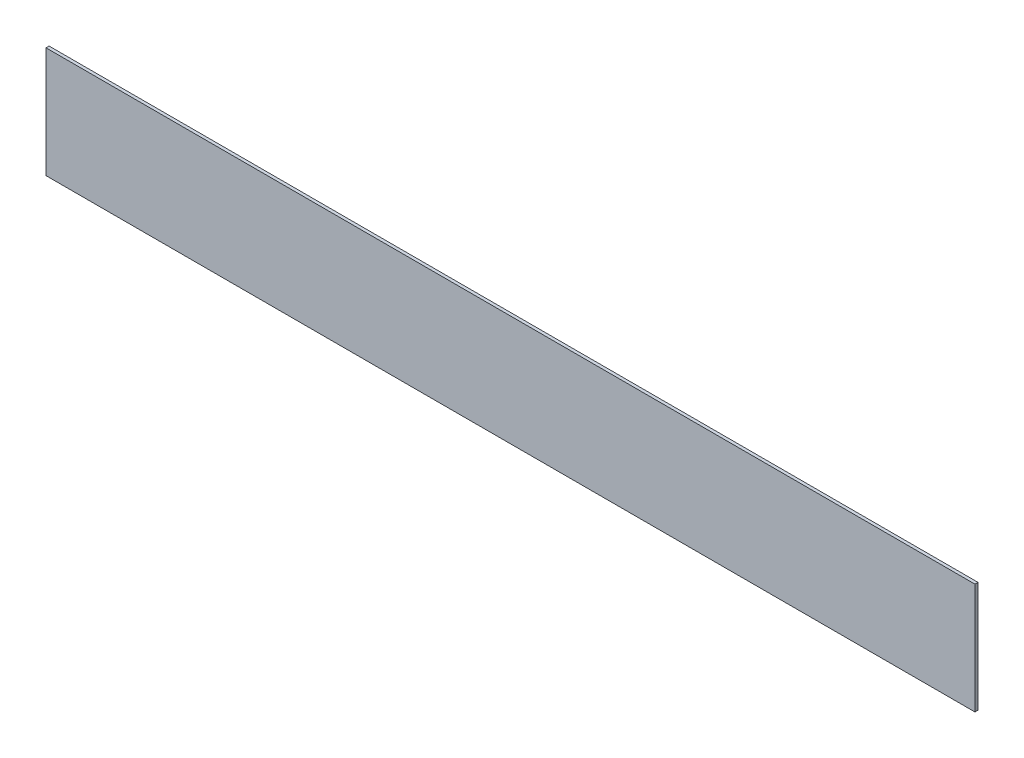
SolidWorks part; units mm, degrees
ref_plane "Front Plane" through (0, 0, 0) normal (0, 0, 1) x (1, 0, 0)
ref_plane "Top Plane" through (0, 0, 0) normal (0, 1, 0) x (1, 0, 0)
ref_plane "Right Plane" through (0, 0, 0) normal (1, 0, 0) x (0, 0, -1)
other "Configuration Table"
sketch "Sketch1" plane through (0, 0, 0) normal (0, 0, 1) x (1, 0, 0)
  line L1 (158, 27) -> (460, 27)
  line L2 (158, 27) -> (158, 63)
  line L3 (158, 63) -> (460, 63)
  line L4 (460, 27) -> (460, 63)
extrude "CEK_donmus_kulp_cukuru_1.0_1" add sketch "Sketch1" along normal blind 1 from offset 26 separate body
